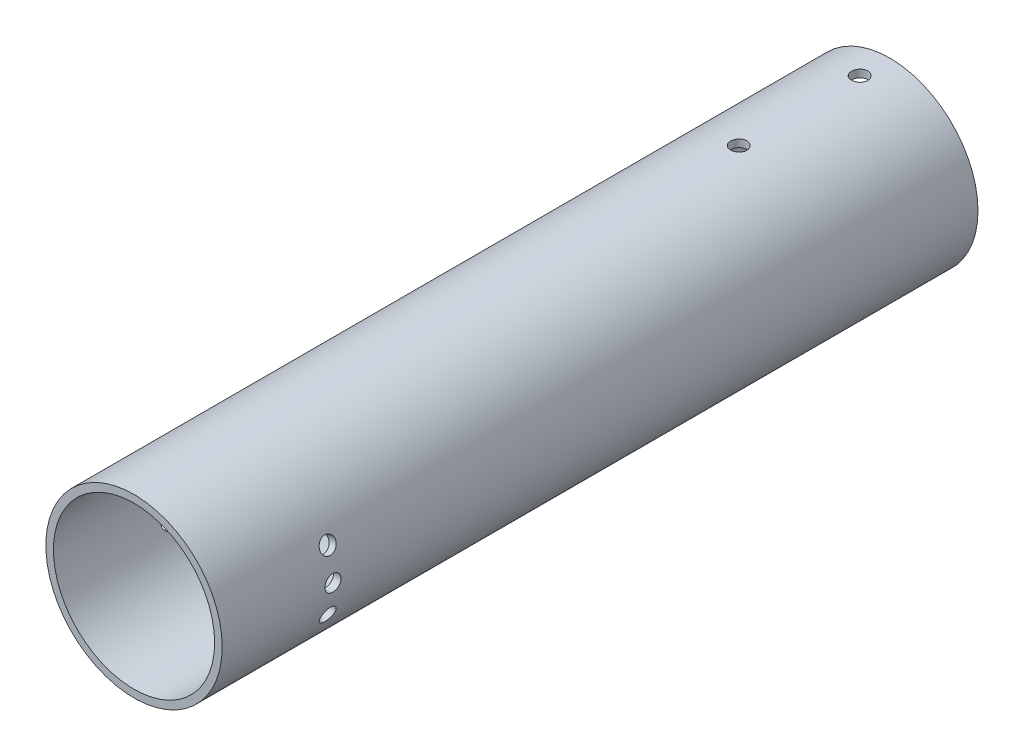
SolidWorks part; units mm, degrees
material "Thornel Mat VMA"
ref_plane "前视基准面" through (0, 0, 0) normal (0, 0, 1) x (1, 0, 0)
ref_plane "上视基准面" through (0, 0, 0) normal (0, 1, 0) x (1, 0, 0)
ref_plane "右视基准面" through (0, 0, 0) normal (1, 0, 0) x (0, 0, -1)
sketch "草图1" plane through (0, 0, 0) normal (0, 0, 1) x (1, 0, 0)
  circle A0 centre (0, 0) radius 17.5
  circle A1 centre (0, 0) radius 16
  dimension "D1" = 35
  dimension "D2" = 32
extrude "凸台-拉伸1" add sketch "草图1" along normal blind 150
sketch "草图2" plane through (0, 0, 0) normal (0, 1, 0) x (1, 0, 0)
  line L0 (0, 0) -> (0, -6) construction
  line L1 (0, -6) -> (0, -30) construction
  circle A0 centre (0, -6) radius 1.6
  circle A1 centre (0, -30) radius 1.6
  dimension "D3" = 3.2
  dimension "D4" = 3.2
  dimension "D1" = 6
  dimension "D2" = 24
extrude "切除-拉伸1" cut sketch "草图2" against normal mid plane 50
ref_plane "基准面1" through (0, 0, 128) normal (0, 0, 1) x (1, 0, 0)
sketch "草图4" plane through (0, 0, 128) normal (0, 0, 1) x (1, 0, 0)
  line L0 (0, 0) -> (0, 32.6127)
  line L1 (0, 0) -> (24.9791, 9.0917)
  dimension "D1" = 70
ref_plane "基准面2" through (24.9791, 9.0917, 128) normal (0.9397, 0.342, 0) x (0.342, -0.9397, 0)
sketch "草图5" plane through (24.9791, 9.0917, 128) normal (0.9397, 0.342, 0) x (0.342, -0.9397, 0)
  line L0 (0, 0) -> (-30.6459, 0) construction
  line L1 (-19.25, 0) -> (19.25, 0) construction
  circle A0 centre (0, 0) radius 1.6
  dimension "D1" = 3.2
extrude "切除-拉伸3" cut sketch "草图5" against normal through all
mirror "镜向1" about plane through (0, 0, 0) normal (1, 0, 0) of "切除-拉伸3"
sketch "草图6" plane through (0, 0, 0) normal (1, 0, 0) x (0, 0, -1)
  line L0 (-128, 19.25) -> (-128, -19.25) construction
  circle A0 centre (-128, 0) radius 1.6
  dimension "D1" = 3.2
extrude "切除-拉伸4" cut sketch "草图6" against normal mid plane 50
